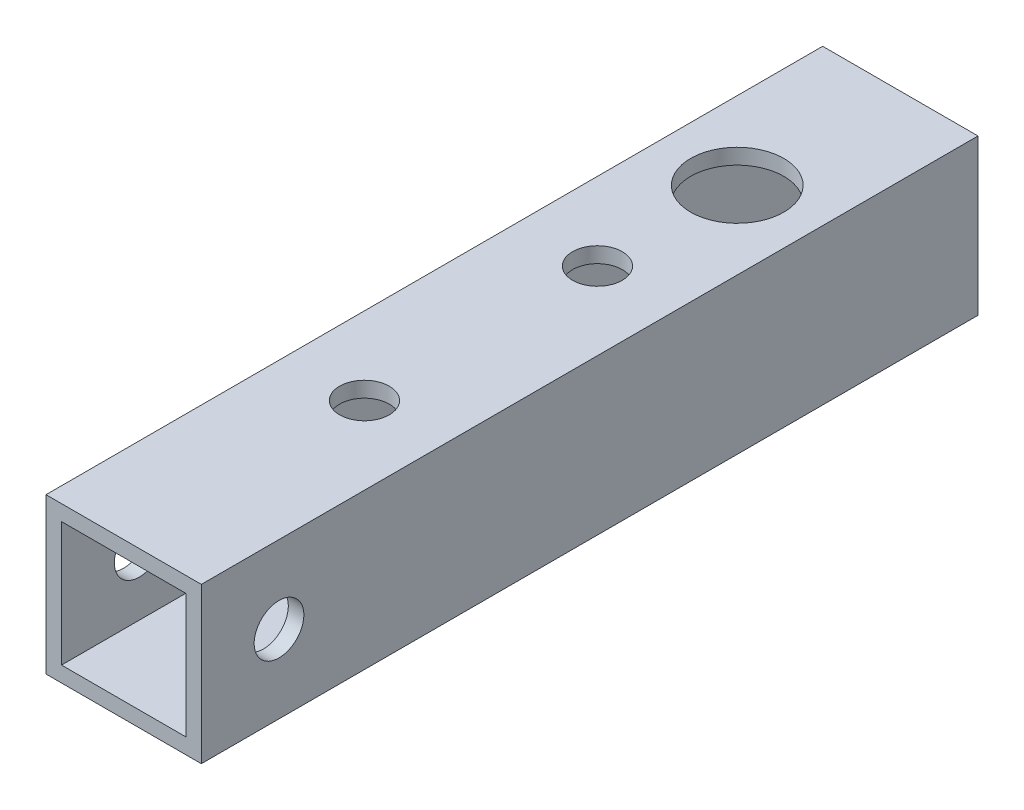
SolidWorks part; units mm, degrees
material "1060 合金"
ref_plane "正面" through (0, 0, 0) normal (0, 0, 1) x (1, 0, 0)
ref_plane "平面" through (0, 0, 0) normal (0, 1, 0) x (1, 0, 0)
ref_plane "右側面" through (0, 0, 0) normal (1, 0, 0) x (0, 0, -1)
sketch "ｽｹｯﾁ1" plane through (0, 0, 0) normal (0, 0, 1) x (1, 0, 0)
  line L1 (0, 0) -> (10, 0)
  line L2 (0, 0) -> (0, 10)
  line L3 (0, 10) -> (10, 10)
  line L4 (10, 0) -> (10, 10)
  dimension "D1" = 10
extrude "押し出し-薄板1" add sketch "ｽｹｯﾁ1" along normal blind 50 thin thin type one direction reverse wall 1
sketch "ｽｹｯﾁ2" plane through (0, 10, 0) normal (0, 1, 0) x (1, 0, 0)
  line L0 (5, 0) -> (5, -50) construction
  line L1 (10, 0) -> (0, 0) construction
  line L2 (10, -50) -> (0, -50) construction
  circle A1 centre (5, -10.5) radius 3
  circle A2 centre (5, -19.5) radius 1.6
  circle A3 centre (5, -34.5) radius 1.6
  dimension "D1" = 3.2
  dimension "D2" = 6
  dimension "D3" = 10.5
  dimension "D5" = 9
  dimension "D6" = 24
extrude "ｶｯﾄ - 押し出し1" cut sketch "ｽｹｯﾁ2" against normal through all
sketch "ｽｹｯﾁ4" plane through (0, 0, 0) normal (0, -1, 0) x (1, 0, 0)
  circle A1 centre (5, 19.5) radius 2.6
  dimension "D1" = 5.2
extrude "ｶｯﾄ - 押し出し2" cut sketch "ｽｹｯﾁ4" against normal up to next
sketch "ｽｹｯﾁ6" plane through (10, 0, 0) normal (1, 0, 0) x (0, 0, -1)
  line L0 (-50, 5) -> (0, 5) construction
  line L1 (-50, 0) -> (-50, 10) construction
  line L2 (0, 0) -> (0, 10) construction
  circle A0 centre (-45, 5) radius 1.6
  dimension "D1" = 3.2
  dimension "D2" = 5
extrude "ｶｯﾄ - 押し出し4" cut sketch "ｽｹｯﾁ6" against normal through all contours A0
